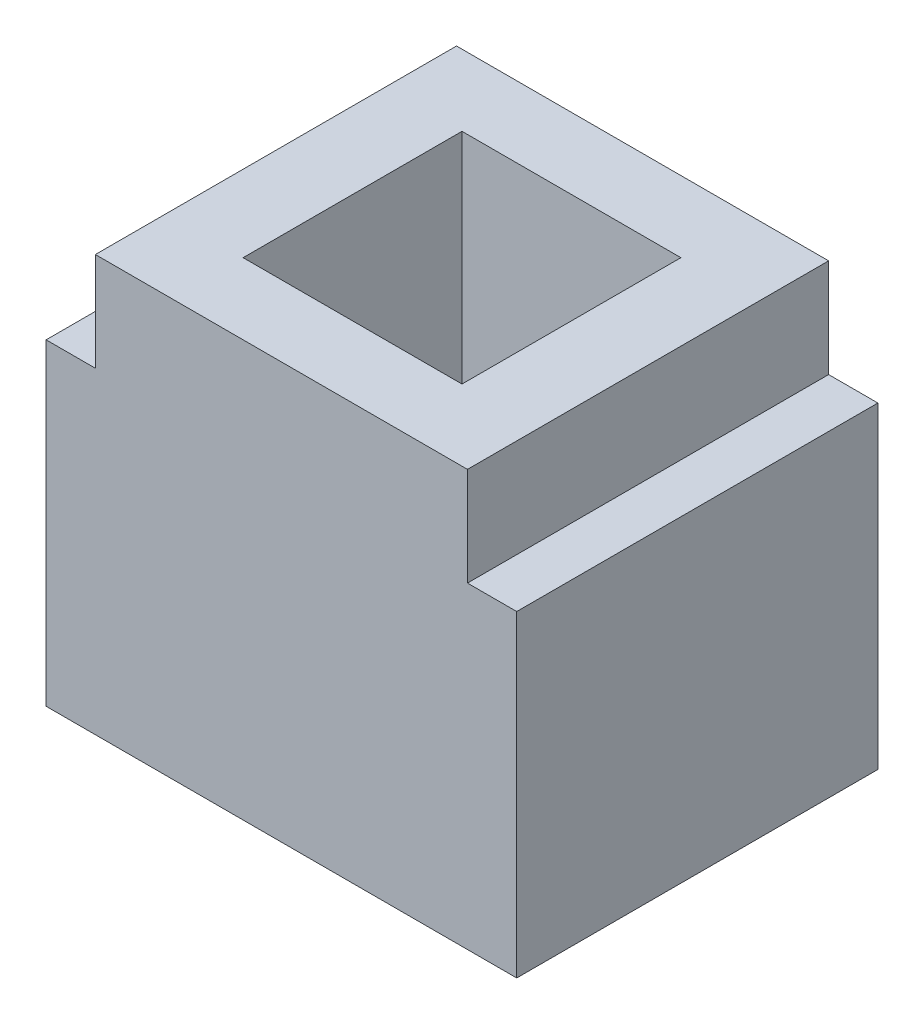
SolidWorks part; units mm, degrees
ref_plane "Alzado" through (0, 0, 0) normal (0, 0, 1) x (1, 0, 0)
ref_plane "Planta" through (0, 0, 0) normal (0, 1, 0) x (1, 0, 0)
ref_plane "Vista lateral" through (0, 0, 0) normal (1, 0, 0) x (0, 0, -1)
sketch "Croquis1" plane through (0, 0, 0) normal (0, 0, 1) x (1, 0, 0)
  line L0 (-43, -29) -> (43, -29)
  line L1 (43, -29) -> (43, 29)
  line L2 (43, 29) -> (34, 29)
  line L3 (34, 29) -> (34, 47)
  line L4 (34, 47) -> (-34, 47)
  line L5 (-34, 47) -> (-34, 29)
  line L6 (-34, 29) -> (-43, 29)
  line L7 (-43, 29) -> (-43, -29)
  point P0 (34.1814, 30.9017)
  point P2 (43, 0)
  point P10 (0, 47)
  dimension "D1" = 86
  dimension "D2" = 58
  dimension "D3" = 76
  dimension "D4" = 68
extrude "Saliente-Extruir1" add sketch "Croquis1" against normal blind 66
sketch "Croquis2" plane through (0, 47, 0) normal (0, 1, 0) x (1, 0, 0)
  line L0 (34, 66) -> (34, 0) construction
  line L1 (-20, 53) -> (20, 53)
  line L2 (-20, 53) -> (-20, 13)
  line L3 (-20, 13) -> (20, 13)
  line L4 (20, 53) -> (20, 13)
  line L5 (34, 66) -> (-34, 66) construction
  point P6 (34, 33)
  point P7 (20, 33)
  point P8 (-20, 33)
  point P11 (0, 66)
  point P12 (0, 53)
  point P13 (0, 13)
  dimension "D1" = 40
extrude "Cortar-Extruir1" cut sketch "Croquis2" against normal blind 50
